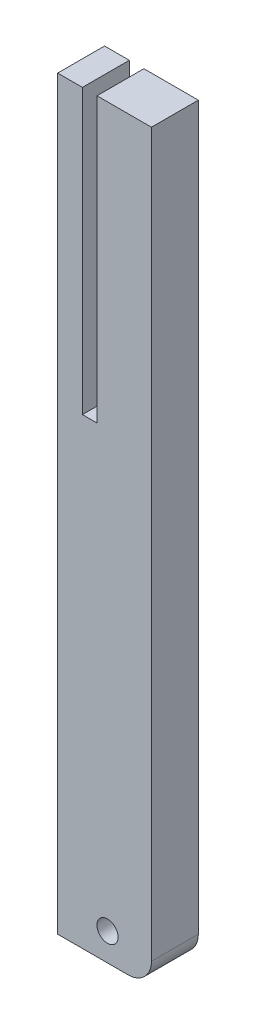
SolidWorks part; units mm, degrees
material "7075-T6, Plate (SS)"
ref_plane "Front Plane" through (0, 0, 0) normal (0, 0, 1) x (1, 0, 0)
ref_plane "Top Plane" through (0, 0, 0) normal (0, 1, 0) x (1, 0, 0)
ref_plane "Right Plane" through (0, 0, 0) normal (1, 0, 0) x (0, 0, -1)
sketch "Sketch1" plane through (0, 0, 0) normal (0, 0, 1) x (1, 0, 0)
  line L2 (-8.3168, -6.7993) -> (1.8432, -6.7993)
  line L3 (1.8432, -6.7993) -> (1.8432, 74.0013)
  line L4 (1.8432, 74.0013) -> (-8.3168, 74.0013)
  line L5 (-8.3168, 74.0013) -> (-8.3168, -6.7993)
  dimension "D1" = 10.16
extrude "Boss-Extrude1" add sketch "Sketch1" along normal blind 5.08
fillet "Fillet1" radius 2.54 1 edges at (1.8432, -6.7993, 2.54)
sketch "Sketch2" plane through (0, 0, 5.08) normal (0, 0, 1) x (1, 0, 0)
  line L0 (1.8432, 74.0013) -> (-8.3168, 74.0013) construction
  line L1 (-5.6356, 74.0013) -> (-4.0562, 74.0013)
  line L2 (-5.6356, 74.0013) -> (-5.6356, 43.2966)
  line L3 (-5.6356, 43.2966) -> (-4.0562, 43.2966)
  line L4 (-4.0562, 74.0013) -> (-4.0562, 43.2966)
  line L7 (-8.3168, -6.7993) -> (-0.6968, -6.7993) construction
  line L8 (-4.8459, 41.154) -> (-4.8459, -6.7993) construction
  line L9 (-5.5647, -3.81) -> (6.0598, -3.81) construction
  line L10 (-5.5647, -2.54) -> (-5.5647, -5.08) construction
  circle A2 centre (-2.9151, -3.81) radius 1.143
  dimension "D2" = 2.286
extrude "Cut-Extrude1" cut sketch "Sketch2" against normal blind 5.08
